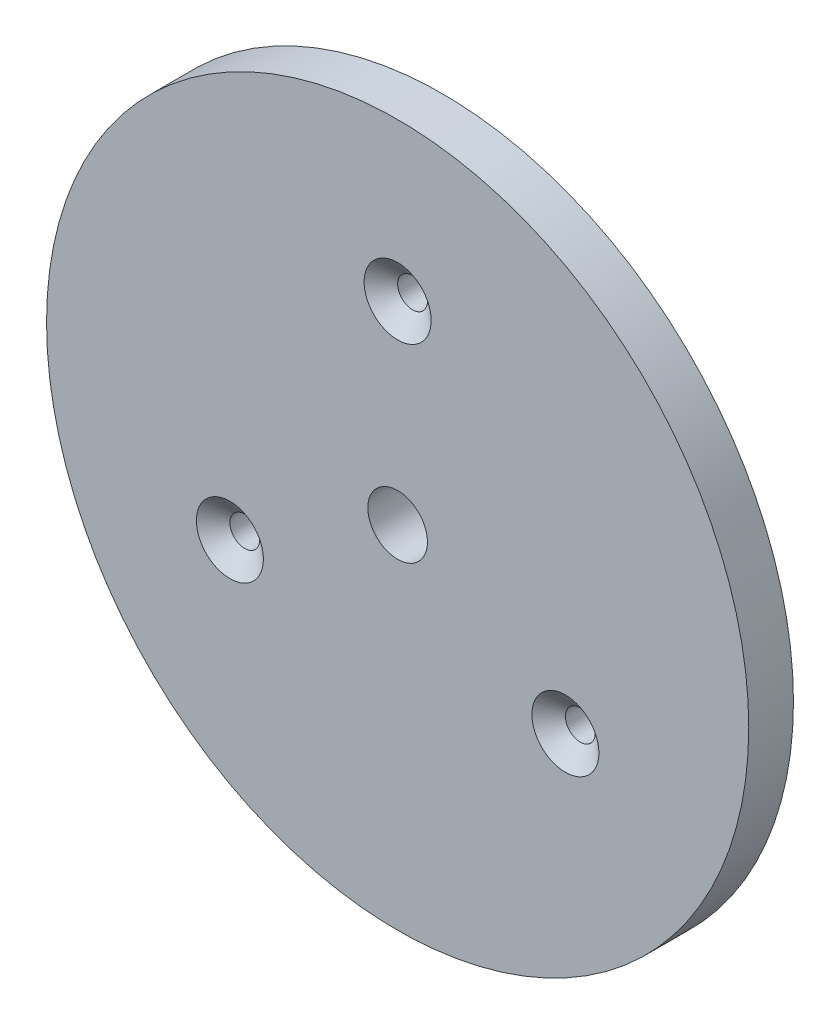
SolidWorks part; units mm, degrees
ref_plane "Front Plane" through (0, 0, 0) normal (1, 0, 0) x (0, 1, 0)
ref_plane "Top Plane" through (0, 0, 0) normal (0, 0, 1) x (0, 1, 0)
ref_plane "Right Plane" through (0, 0, 0) normal (0, 1, 0) x (-1, 0, 0)
sketch "Sketch3" plane through (0, 0, 0) normal (0, 0, 1) x (0, 1, 0)
  circle A0 centre (0, 0) radius 4
  circle A1 centre (0, 0) radius 26 construction
  circle A2 centre (0, 0) radius 47.125
  circle A3 centre (26, 0) radius 2
  circle A4 centre (-13, -22.5167) radius 2
  circle A5 centre (-13, 22.5167) radius 2
  dimension "D1" = 94.25
  dimension "D2" = 8
  dimension "D3" = 52
  dimension "D4" = 4
  dimension "D5" = 3
extrude "Boss-Extrude1" add sketch "Sketch3" along normal blind 6
chamfer "Chamfer1" distance 2.5 distance2 2 3 edges at (-20.5167, -13, 6) (24.5167, -13, 6) (2, 26, 6)
equation "\"SunTeeth\"= 12"
equation "\"PlanetTeeth\" = 40"
equation "\"Module\" = 1"
equation "\"OrbitDiameter\"= \"SunTeeth\" * \"Module\" + \"PlanetTeeth\" * \"Module\""
equation "\"SunBore\"= 8"
equation "\"D1@Sketch3\"= ( \"SunTeeth\" + 2 * \"PlanetTeeth\" ) * \"Module\" + 2.25 * \"Module\""
equation "\"D2@Sketch3\"=\"SunBore\""
equation "\"D3@Sketch3\"=\"OrbitDiameter\""
equation "\"BearingBore\" = 4"
equation "\"D4@Sketch3\"=\"BearingBore\""
equation "\"ScrewCircle\"=31"
equation "\"BearingDiameter\" = 13"
